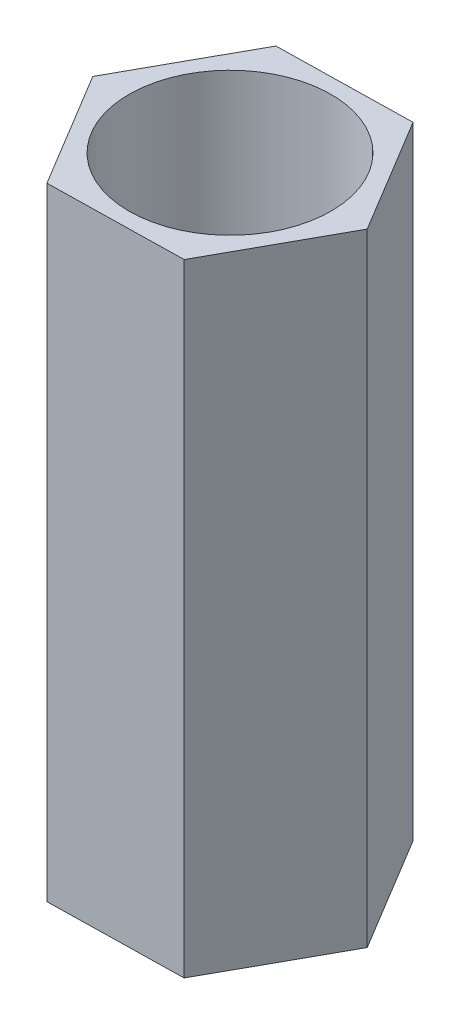
SolidWorks part; units mm, degrees
ref_plane "Front Plane" through (0, 0, 0) normal (0, 0, 1) x (1, 0, 0)
ref_plane "Top Plane" through (0, 0, 0) normal (0, 1, 0) x (1, 0, 0)
ref_plane "Right Plane" through (0, 0, 0) normal (1, 0, 0) x (0, 0, -1)
sketch "Sketch1" plane through (0, 0, 0) normal (0, 1, 0) x (1, 0, 0)
  line L1 (0.8941, -1.4835) -> (1.7317, 0.0326)
  line L2 (1.7317, 0.0326) -> (0.8377, 1.516)
  line L3 (0.8377, 1.516) -> (-0.8941, 1.4835)
  line L4 (-0.8941, 1.4835) -> (-1.7317, -0.0326)
  line L5 (-1.7317, -0.0326) -> (-0.8377, -1.516)
  line L6 (-0.8377, -1.516) -> (0.8941, -1.4835)
  circle A0 centre (0, 0) radius 1.5 construction
  circle A1 centre (0, 0) radius 1.3
  dimension "D1" = 3
  dimension "D2" = 2.6
extrude "Boss-Extrude1" add sketch "Sketch1" along normal blind 8
